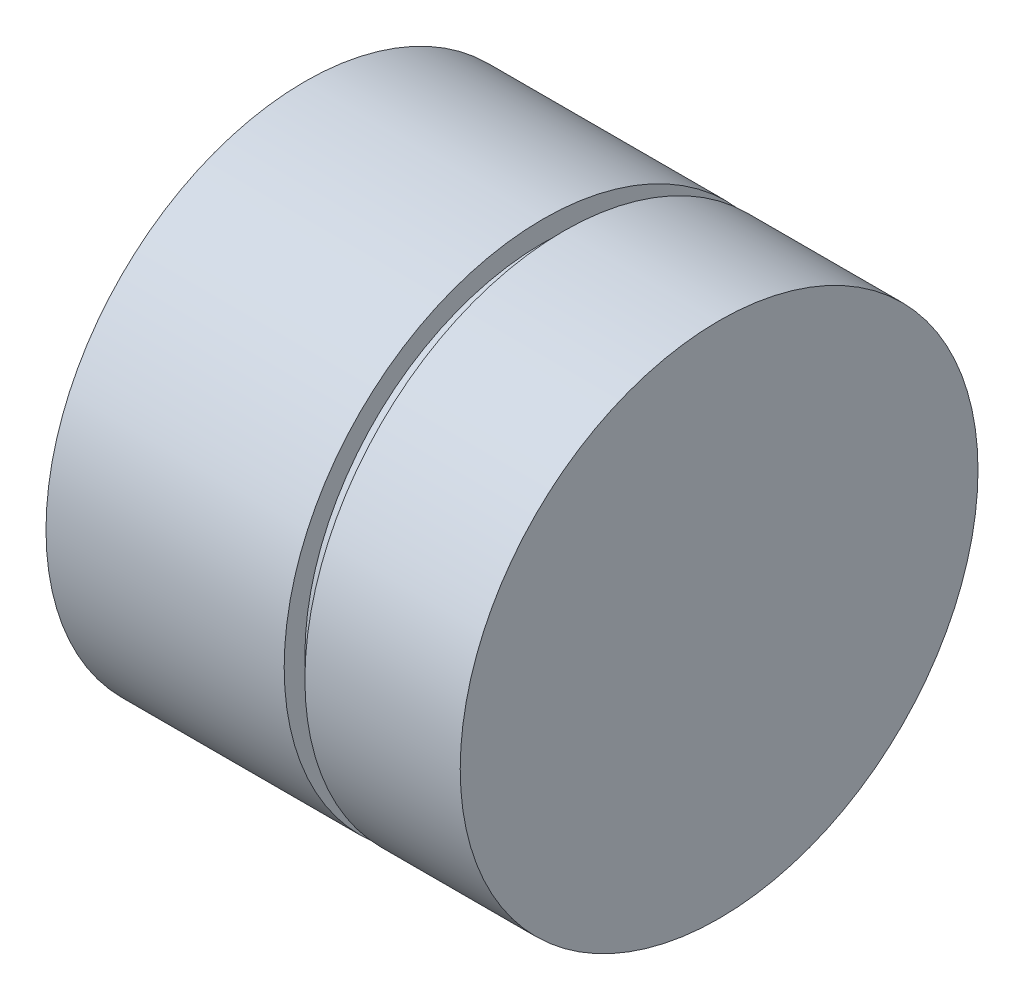
SolidWorks part; units mm, degrees
material "延性铁"
ref_plane "前视基准面" through (0, 0, 0) normal (0, 0, 1) x (1, 0, 0)
ref_plane "上视基准面" through (0, 0, 0) normal (0, 1, 0) x (1, 0, 0)
ref_plane "右视基准面" through (0, 0, 0) normal (1, 0, 0) x (0, 0, -1)
sketch "草图1" plane through (0, 0, 0) normal (1, 0, 0) x (0, 0, -1)
  circle A0 centre (0, 0) radius 2.5
extrude "凸台-拉伸1" add sketch "草图1" along normal blind 2.5
sketch "草图3" plane through (2.5, 0, 0) normal (1, 0, 0) x (0, 0, -1)
  circle A1 centre (0, 0) radius 2.4
extrude "凸台-拉伸4" add sketch "草图3" along normal blind 1.5
sketch "草图4" plane through (2.5, 0, 0) normal (1, 0, 0) x (0, 0, -1)
  circle A0 centre (0, 0) radius 2.3
  circle A1 centre (0, 0) radius 2.5
extrude "切除-拉伸2" cut sketch "草图4" against normal blind 0.2
sketch "草图5" plane through (2.5, 0, 0) normal (-1, 0, 0) x (0, 0, 1)
  circle A0 centre (0, 0) radius 2.5
  circle A1 centre (0, 0) radius 2.4
extrude "凸台-拉伸5" add sketch "草图5" against normal blind 1.5
sketch "草图6" plane through (0, 0, 0) normal (-1, 0, 0) x (0, 0, 1)
  circle A0 centre (0, 0) radius 0.5
extrude "切除-拉伸3" cut sketch "草图6" against normal blind 0.4
sketch "草图7" plane through (0, 0, 0) normal (-1, 0, 0) x (0, 0, 1)
  circle A1 centre (0, 1) radius 0.15
  circle A2 centre (-0.866, -0.5) radius 0.15
  circle A3 centre (0.866, -0.5) radius 0.15
extrude "切除-拉伸4" cut sketch "草图7" against normal blind 0.8
